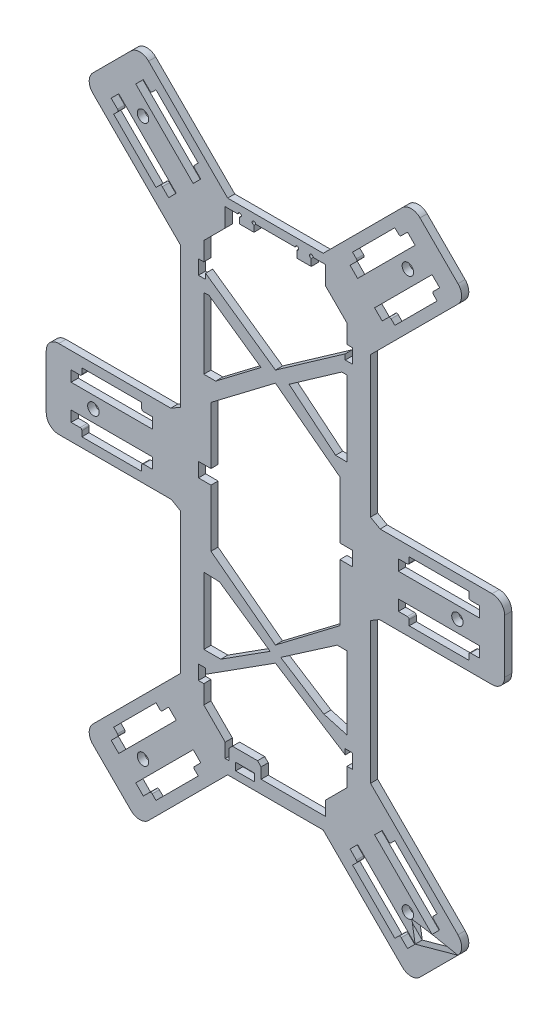
SolidWorks part; units mm, degrees
ref_plane "前视基准面" through (0, 0, 0) normal (0, 0, 1) x (1, 0, 0)
ref_plane "上视基准面" through (0, 0, 0) normal (0, 1, 0) x (1, 0, 0)
ref_plane "右视基准面" through (0, 0, 0) normal (1, 0, 0) x (0, 0, -1)
sketch "草图1" plane through (0, 0, 0) normal (0, 0, 1) x (1, 0, 0)
  line L0 (-44.1032, 75.8899) -> (-45.8709, 77.6577) construction
  line L1 (-36.8907, 86.638) -> (-35.1229, 84.8702)
  line L2 (-34.4158, 84.8702) -> (-33.3551, 85.9309)
  line L3 (-44.1032, 75.8899) -> (-45.8709, 77.6577)
  line L4 (-45.8709, 77.6577) -> (-43.7496, 79.779)
  line L5 (-32.2945, 63.3742) -> (-33.3551, 62.3135)
  line L6 (-33.3551, 85.9309) -> (-21.5465, 74.1222)
  line L7 (-26.5563, 51.8432) -> (-26.5563, 12.5444)
  line L8 (-53.4515, 78.7384) -> (-26.5563, 51.8432)
  line L9 (-27.6983, 63.7277) -> (-29.8196, 61.6064)
  line L10 (-22.9607, 68.4653) -> (-39.012, 84.5167)
  line L11 (-20.8394, 70.5866) -> (-22.9607, 68.4653)
  line L12 (-43.7496, 79.779) -> (-27.6983, 63.7277)
  line L13 (-33.3551, 62.3135) -> (-45.1638, 74.1222)
  line L14 (-22.6071, 72.3544) -> (-20.8394, 70.5866)
  line L15 (-13.3431, 69.7427) -> (-37.8952, 94.2947)
  line L16 (13.3431, 69.7427) -> (-13.3431, 69.7427)
  line L17 (-39.012, 84.5167) -> (-36.8907, 86.638)
  line L18 (-29.8196, 61.6064) -> (-31.5874, 63.3742)
  line L19 (-21.5465, 74.1222) -> (-22.6071, 73.0615)
  line L20 (-54.0527, 6.85) -> (-54.0527, 8.35) construction
  line L21 (-45.1638, 74.1222) -> (-44.1032, 75.1828)
  line L22 (-44.1032, -75.8899) -> (-45.8709, -77.6577) construction
  line L23 (-45.1638, -74.1222) -> (-44.1032, -75.1828)
  line L24 (-21.5465, -74.1222) -> (-22.6071, -73.0615)
  line L25 (26.5563, 12.5444) -> (26.5563, 51.8432)
  line L26 (29.2297, 11) -> (26.5563, 12.5444)
  line L27 (29.2297, 11) -> (64.0054, 11)
  line L28 (64.0054, 11) -> (64.0054, -11)
  line L29 (64.0054, -11) -> (29.0331, -11)
  line L30 (0, 0) -> (64.0054, 0) construction
  line L31 (-29.8196, -61.6064) -> (-31.5874, -63.3742)
  line L32 (26.5563, -12.4665) -> (29.0331, -11)
  line L33 (26.5563, -51.8432) -> (26.5563, -12.4665)
  line L34 (-39.012, -84.5167) -> (-36.8907, -86.638)
  line L35 (-22.6071, -72.3544) -> (-20.8394, -70.5866)
  line L36 (-33.3551, -62.3135) -> (-45.1638, -74.1222)
  line L37 (-43.7496, -79.779) -> (-27.6983, -63.7277)
  line L38 (-20.8394, -70.5866) -> (-22.9607, -68.4653)
  line L39 (-22.9607, -68.4653) -> (-39.012, -84.5167)
  line L40 (-27.6983, -63.7277) -> (-29.8196, -61.6064)
  line L41 (-33.3551, -85.9309) -> (-21.5465, -74.1222)
  line L42 (53.4515, -78.7384) -> (26.5563, -51.8432)
  line L43 (13.3431, -69.7427) -> (37.8952, -94.2947)
  line L44 (-32.2945, -63.3742) -> (-33.3551, -62.3135)
  line L45 (-45.8709, -77.6577) -> (-43.7496, -79.779)
  line L46 (-44.1032, -75.8899) -> (-45.8709, -77.6577)
  line L47 (-34.4158, -84.8702) -> (-33.3551, -85.9309)
  line L48 (37.8952, -94.2947) -> (53.4515, -78.7384)
  line L49 (-36.8907, -86.638) -> (-35.1229, -84.8702)
  line L50 (44.1032, -75.8899) -> (45.8709, -77.6577) construction
  line L51 (-26.5563, -12.4665) -> (-26.5563, -51.8432)
  line L52 (36.8907, -86.638) -> (35.1229, -84.8702)
  line L53 (34.4158, -84.8702) -> (33.3551, -85.9309)
  line L54 (44.1032, -75.8899) -> (45.8709, -77.6577)
  line L55 (45.8709, -77.6577) -> (43.7496, -79.779)
  line L56 (32.2945, -63.3742) -> (33.3551, -62.3135)
  line L57 (33.3551, -85.9309) -> (21.5465, -74.1222)
  line L58 (27.6983, -63.7277) -> (29.8196, -61.6064)
  line L59 (22.9607, -68.4653) -> (39.012, -84.5167)
  line L60 (20.8394, -70.5866) -> (22.9607, -68.4653)
  line L61 (43.7496, -79.779) -> (27.6983, -63.7277)
  line L62 (33.3551, -62.3135) -> (45.1638, -74.1222)
  line L63 (22.6071, -72.3544) -> (20.8394, -70.5866)
  line L64 (-37.8952, -94.2947) -> (-53.4515, -78.7384)
  line L65 (39.012, -84.5167) -> (36.8907, -86.638)
  line L66 (29.8196, -61.6064) -> (31.5874, -63.3742)
  line L67 (21.5465, -74.1222) -> (22.6071, -73.0615)
  line L68 (-5.9, -65.5642) -> (-11.1, -65.5642)
  line L69 (-11.1, -65.5642) -> (-11.1, -67.6642)
  line L70 (-11.1, -67.6642) -> (-5.9, -67.6642)
  line L71 (-5.9, -67.6642) -> (-5.9, -65.5642)
  line L72 (13.529, -41.6245) -> (20, -43.441)
  line L73 (20, -43.441) -> (20, -23.0831)
  line L74 (20, -23.0831) -> (17.2397, -23.0831)
  line L75 (17.2397, -23.0831) -> (1.471, -33.9277)
  line L76 (1.471, -33.9277) -> (13.529, -41.6245)
  line L77 (-1.471, -33.9277) -> (-15.6081, -24.2051)
  line L78 (-15.6081, -24.2051) -> (-20, -24.0377)
  line L79 (-20, -24.0377) -> (-20, -42.7305)
  line L80 (-14.0147, -66.1421) -> (-13, -66.1421)
  line L81 (-13, -66.1421) -> (-13, -63.1421)
  line L82 (-13, -63.1421) -> (-12, -62.1421)
  line L83 (-12, -62.1421) -> (-5, -62.1421)
  line L84 (-5, -62.1421) -> (-4, -63.1421)
  line L85 (-4, -63.1421) -> (-4, -66.1421)
  line L86 (-4, -66.1421) -> (14.0147, -66.1421)
  line L87 (14.0147, -66.1421) -> (14.0147, -62.1568)
  line L88 (14.0147, -62.1568) -> (20, -56.1716)
  line L89 (20, -56.1716) -> (20, -51)
  line L90 (20, -51) -> (21.5, -51)
  line L91 (21.5, -51) -> (21.5, -47)
  line L92 (0, 67.3431) -> (0, -67.3431) construction
  line L93 (45.1638, -74.1222) -> (44.1032, -75.1828)
  line L94 (54.0527, 6.85) -> (54.0527, 8.35) construction
  line L95 (54.0527, 8.35) -> (54.0527, 6.85)
  line L96 (54.5527, 6.35) -> (57.0527, 6.35)
  line L97 (-37.8952, 94.2947) -> (-53.4515, 78.7384)
  line L98 (57.0527, 6.35) -> (57.0527, 3.35)
  line L99 (57.0527, 3.35) -> (34.3527, 3.35)
  line L100 (34.3527, 3.35) -> (34.3527, 6.35)
  line L101 (-26.5563, -12.4665) -> (-29.0331, -11)
  line L102 (-64.0054, -11) -> (-29.0331, -11)
  line L103 (-64.0054, 11) -> (-64.0054, -11)
  line L104 (-29.2297, 11) -> (-64.0054, 11)
  line L105 (-29.2297, 11) -> (-26.5563, 12.5444)
  line L106 (34.3527, 6.35) -> (36.8527, 6.35)
  line L107 (37.3527, 6.85) -> (37.3527, 8.35)
  line L108 (37.3527, 8.35) -> (54.0527, 8.35)
  line L109 (54.0527, -6.85) -> (54.0527, -8.35)
  line L110 (54.0527, -8.35) -> (37.3527, -8.35)
  line L111 (37.3527, -8.35) -> (37.3527, -6.85)
  line L112 (36.8527, -6.35) -> (34.3527, -6.35)
  line L113 (34.3527, -6.35) -> (34.3527, -3.35)
  line L114 (34.3527, -3.35) -> (57.0527, -3.35)
  line L115 (57.0527, -3.35) -> (57.0527, -6.35)
  line L116 (57.0527, -6.35) -> (54.5527, -6.35)
  line L117 (-30.9863, 76.491) -> (-35.724, 71.7534) construction
  line L118 (30.9863, 76.491) -> (35.724, 71.7534) construction
  line L119 (21.5, 2) -> (21.5, -2)
  line L120 (-21.5, 2) -> (-21.5, -2)
  line L128 (44.1032, 75.8899) -> (45.8709, 77.6577) construction
  line L133 (37.8952, 94.2947) -> (53.4515, 78.7384)
  line L138 (13.3431, 69.7427) -> (37.8952, 94.2947)
  line L139 (53.4515, 78.7384) -> (26.5563, 51.8432)
  line L146 (21.5, -47) -> (19.5, -47)
  line L147 (19.5, -47) -> (19.5, -48.5)
  line L148 (19.5, -48.5) -> (0, -36.0529)
  line L149 (0, -36.0529) -> (-19.5, -48.5)
  line L150 (-19.5, -48.5) -> (-19.5, -47)
  line L151 (-19.5, -47) -> (-21.5, -47)
  line L152 (-21.5, -47) -> (-21.5, -51)
  line L153 (-21.5, -51) -> (-20, -51)
  line L154 (13.3431, -69.7427) -> (-13.3431, -69.7427)
  line L155 (-13.3431, -69.7427) -> (-37.8952, -94.2947)
  line L161 (-53.4515, -78.7384) -> (-26.5563, -51.8432)
  line L162 (-20, -51) -> (-20, -56.1716)
  line L163 (-20, -56.1716) -> (-14.0147, -62.1568)
  line L164 (-14.0147, -62.1568) -> (-14.0147, -66.1421)
  line L165 (-20, -42.7305) -> (-15.2617, -42.7305)
  line L166 (-15.2617, -42.7305) -> (-1.471, -33.9277)
  line L167 (-4.0182, 33.4407) -> (-18.5351, 43.6186)
  line L168 (-18.5351, 43.6186) -> (-20.0019, 43.5627)
  line L169 (-20.0019, 43.5627) -> (-20.0019, 23.8211)
  line L170 (-20.0019, 23.8211) -> (-16.6834, 23.8211)
  line L171 (18, -2) -> (21.5, -2)
  line L173 (21.5, 2) -> (18, 2)
  line L174 (18, 2) -> (18, 18)
  line L175 (18, 18) -> (0, 31.6716)
  line L176 (0, 31.6716) -> (-18, 18)
  line L177 (-18, 18) -> (-18, 2)
  line L178 (-18, 2) -> (-21.5, 2)
  line L180 (-21.5, -2) -> (-18, -2)
  line L181 (-18, -2) -> (-18, -18)
  line L182 (-18, -18) -> (0, -31.6716)
  line L183 (0, -31.6716) -> (18, -18)
  line L184 (18, -18) -> (18, -2)
  line L185 (-16.6834, 23.8211) -> (-4.0182, 33.4407)
  line L186 (16.8026, 22.6188) -> (20.0019, 22.5893)
  line L187 (20.0019, 22.5893) -> (20.0019, 43.6186)
  line L188 (20.0019, 43.6186) -> (18.5351, 43.6186)
  line L189 (18.5351, 43.6186) -> (3.8079, 33.2932)
  line L190 (3.8079, 33.2932) -> (16.8026, 22.6188)
  line L191 (-20, 56.1716) -> (-20, 51)
  line L192 (-20, 51) -> (-21.5, 51)
  line L193 (-21.5, 51) -> (-21.5, 47)
  line L194 (-21.5, 47) -> (-19.5, 47)
  line L195 (-19.5, 47) -> (-19.5, 48.5)
  line L196 (-19.5, 48.5) -> (0, 34.8284)
  line L197 (0, 34.8284) -> (19.5, 48.5)
  line L198 (19.5, 48.5) -> (19.5, 47)
  line L199 (19.5, 47) -> (21.5, 47)
  line L200 (21.5, 47) -> (21.5, 51)
  line L201 (21.5, 51) -> (20, 51)
  line L202 (20, 51) -> (20, 56.1716)
  line L203 (20, 56.1716) -> (14.0147, 62.1568)
  line L204 (14.0147, 62.1568) -> (14.0147, 67.3431)
  line L205 (14.0147, 67.3431) -> (10.5, 67.3431)
  line L206 (10, 66.8431) -> (10, 64.8715)
  line L207 (10, 64.8715) -> (6, 64.8715)
  line L208 (6, 64.8715) -> (6, 66.8431)
  line L209 (5.5, 67.3431) -> (-5.5, 67.3431)
  line L210 (-6, 66.8431) -> (-6, 65.1418)
  line L211 (-6, 65.1418) -> (-10, 65.1418)
  line L212 (-10, 65.1418) -> (-10, 66.8431)
  line L213 (-10.5, 67.3431) -> (-14.0147, 67.3431)
  line L214 (-14.0147, 67.3431) -> (-14.0147, 62.1568)
  line L215 (-14.0147, 62.1568) -> (-20, 56.1716)
  line L216 (-57.0527, -6.35) -> (-54.5527, -6.35)
  line L217 (-57.0527, -3.35) -> (-57.0527, -6.35)
  line L218 (-34.3527, -3.35) -> (-57.0527, -3.35)
  line L219 (-34.3527, -6.35) -> (-34.3527, -3.35)
  line L220 (-36.8527, -6.35) -> (-34.3527, -6.35)
  line L221 (-37.3527, -8.35) -> (-37.3527, -6.85)
  line L222 (-54.0527, -8.35) -> (-37.3527, -8.35)
  line L223 (-54.0527, -6.85) -> (-54.0527, -8.35)
  line L224 (-37.3527, 8.35) -> (-54.0527, 8.35)
  line L225 (-37.3527, 6.85) -> (-37.3527, 8.35)
  line L226 (-34.3527, 6.35) -> (-36.8527, 6.35)
  line L227 (-34.3527, 3.35) -> (-34.3527, 6.35)
  line L228 (-57.0527, 3.35) -> (-34.3527, 3.35)
  line L229 (-57.0527, 6.35) -> (-57.0527, 3.35)
  line L230 (-54.5527, 6.35) -> (-57.0527, 6.35)
  line L231 (-54.0527, 8.35) -> (-54.0527, 6.85)
  line L232 (45.1638, 74.1222) -> (44.1032, 75.1828)
  line L233 (21.5465, 74.1222) -> (22.6071, 73.0615)
  line L234 (29.8196, 61.6064) -> (31.5874, 63.3742)
  line L235 (39.012, 84.5167) -> (36.8907, 86.638)
  line L236 (22.6071, 72.3544) -> (20.8394, 70.5866)
  line L237 (33.3551, 62.3135) -> (45.1638, 74.1222)
  line L238 (43.7496, 79.779) -> (27.6983, 63.7277)
  line L239 (20.8394, 70.5866) -> (22.9607, 68.4653)
  line L240 (22.9607, 68.4653) -> (39.012, 84.5167)
  line L241 (27.6983, 63.7277) -> (29.8196, 61.6064)
  line L242 (33.3551, 85.9309) -> (21.5465, 74.1222)
  line L243 (32.2945, 63.3742) -> (33.3551, 62.3135)
  line L244 (45.8709, 77.6577) -> (43.7496, 79.779)
  line L245 (44.1032, 75.8899) -> (45.8709, 77.6577)
  line L246 (34.4158, 84.8702) -> (33.3551, 85.9309)
  line L247 (36.8907, 86.638) -> (35.1229, 84.8702)
  arc A0 (-44.1032, 75.8899) -> (-44.1032, 75.1828) centre (-44.4567, 75.5364) cw
  circle A1 centre (-36.9826, 77.7496) radius 1.6
  arc A2 (-34.4158, 84.8702) -> (-35.1229, 84.8702) centre (-34.7694, 85.2238) cw
  arc A3 (-22.6071, 72.3544) -> (-22.6071, 73.0615) centre (-22.2536, 72.708) cw
  arc A4 (-32.2945, 63.3742) -> (-31.5874, 63.3742) centre (-31.9409, 63.0206) cw
  arc A5 (-32.2945, -63.3742) -> (-31.5874, -63.3742) centre (-31.9409, -63.0206) ccw
  arc A6 (-22.6071, -72.3544) -> (-22.6071, -73.0615) centre (-22.2536, -72.708) ccw
  arc A7 (-34.4158, -84.8702) -> (-35.1229, -84.8702) centre (-34.7694, -85.2238) ccw
  arc A8 (54.5527, 6.35) -> (54.0527, 6.85) centre (54.5527, 6.85) cw
  arc A9 (37.3527, 6.85) -> (36.8527, 6.35) centre (36.8527, 6.85) cw
  circle A10 centre (-36.9826, -77.7496) radius 1.6
  arc A11 (-44.1032, -75.8899) -> (-44.1032, -75.1828) centre (-44.4567, -75.5364) ccw
  arc A12 (44.1032, -75.8899) -> (44.1032, -75.1828) centre (44.4567, -75.5364) cw
  circle A13 centre (36.9826, -77.7496) radius 1.6
  arc A14 (34.4158, -84.8702) -> (35.1229, -84.8702) centre (34.7694, -85.2238) cw
  arc A15 (54.0527, -6.85) -> (54.5527, -6.35) centre (54.5527, -6.85) cw
  arc A16 (22.6071, -72.3544) -> (22.6071, -73.0615) centre (22.2536, -72.708) cw
  arc A17 (32.2945, -63.3742) -> (31.5874, -63.3742) centre (31.9409, -63.0206) cw
  arc A18 (36.8527, -6.35) -> (37.3527, -6.85) centre (36.8527, -6.85) cw
  circle A19 centre (50.8327, 0) radius 1.6
  arc A76 (10.5, 67.3431) -> (10, 66.8431) centre (10, 67.3431) ccw
  arc A77 (6, 66.8431) -> (5.5, 67.3431) centre (6, 67.3431) ccw
  arc A78 (-5.5, 67.3431) -> (-6, 66.8431) centre (-6, 67.3431) ccw
  arc A79 (-10, 66.8431) -> (-10.5, 67.3431) centre (-10, 67.3431) ccw
  circle A80 centre (-50.8327, 0) radius 1.6
  arc A81 (-36.8527, -6.35) -> (-37.3527, -6.85) centre (-36.8527, -6.85) ccw
  arc A82 (-54.0527, -6.85) -> (-54.5527, -6.35) centre (-54.5527, -6.85) ccw
  arc A83 (-37.3527, 6.85) -> (-36.8527, 6.35) centre (-36.8527, 6.85) ccw
  arc A84 (-54.5527, 6.35) -> (-54.0527, 6.85) centre (-54.5527, 6.85) ccw
  arc A85 (32.2945, 63.3742) -> (31.5874, 63.3742) centre (31.9409, 63.0206) ccw
  arc A86 (22.6071, 72.3544) -> (22.6071, 73.0615) centre (22.2536, 72.708) ccw
  arc A87 (34.4158, 84.8702) -> (35.1229, 84.8702) centre (34.7694, 85.2238) ccw
  circle A88 centre (36.9826, 77.7496) radius 1.6
  arc A89 (44.1032, 75.8899) -> (44.1032, 75.1828) centre (44.4567, 75.5364) ccw
  dimension "D1" = 4
  dimension "D2" = 4
  dimension "D3" = 45
  dimension "D4" = 22
  dimension "D5" = 22
  dimension "D6" = 4
  dimension "D7" = 45
  dimension "D8" = 26.5563
  dimension "D9" = 43
  dimension "D10" = 2
  dimension "D11" = 2
extrude "凸台-拉伸1" add sketch "草图1" along normal blind 2
fillet "圆角1" radius 3.5 12 edges at (53.4515, -78.7384, 1) (37.8952, -94.2947, 1) (-37.8952, -94.2947, 1) (-53.4515, -78.7384, 1) (-64.0054, -11, 1) (-64.0054, 11, 1) (64.0054, -11, 1) (64.0054, 11, 1) (53.4515, 78.7384, 1) (37.8952, 94.2947, 1) (-53.4515, 78.7384, 1) (-37.8952, 94.2947, 1)
